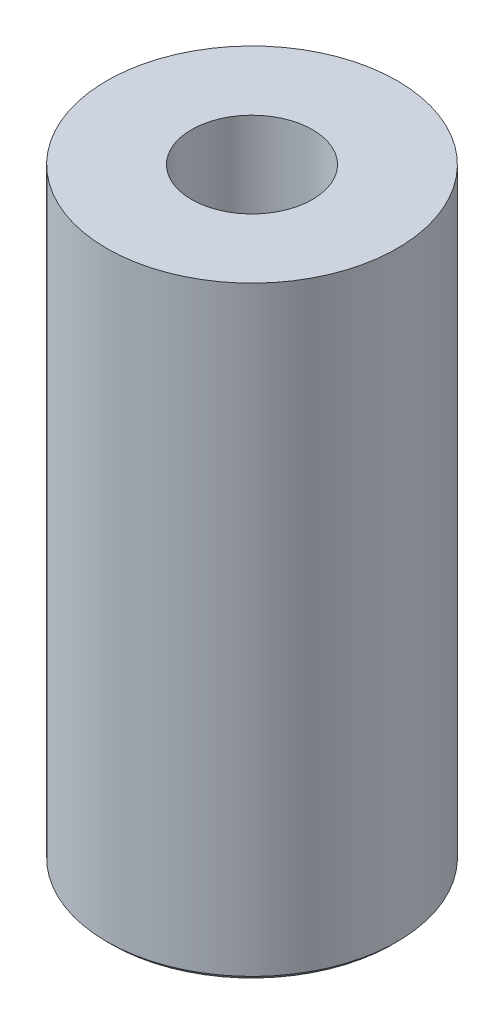
SolidWorks part; units mm, degrees
ref_plane "Front Plane" through (0, 0, 0) normal (0, 0, 1) x (1, 0, 0)
ref_plane "Top Plane" through (0, 0, 0) normal (0, 1, 0) x (1, 0, 0)
ref_plane "Right Plane" through (0, 0, 0) normal (1, 0, 0) x (0, 0, -1)
other "Configuration Table"
sketch "草图1" plane through (0, 0, 0) normal (0, 1, 0) x (1, 0, 0)
  circle A0 centre (0, 0) radius 6
extrude "凸台-拉伸1" add sketch "草图1" along normal blind 25
sketch "草图4" plane through (0, 25, 0) normal (0, 1, 0) x (1, 0, 0)
  point P0 (0, 0)
hole_wizard "M6x1.0 螺纹孔1" positions "草图4" profile "草图3" tap size "M6x1.0" standard "ANSI Metric"
cosmetic thread "孔螺纹线1" parameters "D1"=4, "D2"=6
sketch "草图3" plane through (0, 25, 0) normal (1, 0, 0) x (0, 0, 1)
  line L0 (0, 0) -> (0, 7.5022)
  line L1 (0, 7.5022) -> (2.5, 6)
  line L2 (2.5, 6) -> (2.5, 0)
  line L5 (2.5, 0) -> (0, 0)
  line L10 (0, 7.5022) -> (-2.5, 6) construction
  line L11 (0, -6.35) -> (0, 107.95) construction
  dimension "螺纹孔钻头直径" = 5
  dimension "螺纹孔钻头深度" = 6
  dimension "导头角度" = 118
chamfer "倒角1" distance 0.2 angle 45 1 edges at (0, 0, 6)
